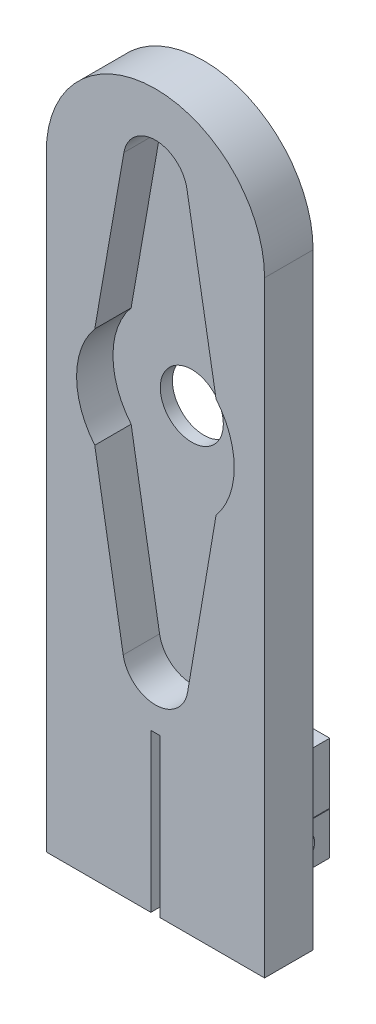
SolidWorks part; units mm, degrees
ref_plane "前基準面" through (0, 0, 0) normal (0, 0, 1) x (1, 0, 0)
ref_plane "上基準面" through (0, 0, 0) normal (0, 1, 0) x (1, 0, 0)
ref_plane "右基準面" through (0, 0, 0) normal (1, 0, 0) x (0, 0, -1)
sketch "草圖1" plane through (0, 0, 0) normal (0, 0, 1) x (1, 0, 0)
  line L0 (-9, 0) -> (-9, 50)
  line L1 (0, 45.5769) -> (0, 0) construction
  line L2 (-9, 0) -> (9, 0)
  line L3 (9, 0) -> (9, 50)
  arc A0 (-9, 50) -> (9, 50) centre (0, 50) cw
  dimension "D1" = 18
  dimension "D2" = 50
extrude "填料-伸長1" add sketch "草圖1" along normal blind 4 contours L3 A0 L0 L2
sketch "草圖2" plane through (0, 0, 4) normal (0, 0, 1) x (1, 0, 0)
  line L0 (-2.6, 53.1451) -> (-5, 39.3524)
  line L1 (2.6, 53.1451) -> (5, 39.3524)
  line L2 (-5, 31.0457) -> (-2.6563, 17.2433)
  line L3 (5, 31.0457) -> (2.6563, 17.2433)
  line L5 (0, 0) -> (0, 15) construction
  line L6 (0, 55.3318) -> (0, 46.5984) construction
  line L7 (0, 15.3887) -> (0, 39.6759) construction
  line L8 (-9, 0) -> (9, 0) construction
  arc A0 (-2.6563, 17.2433) -> (2.6563, 17.2433) centre (0, 17.6943) ccw
  arc A1 (2.6, 53.1451) -> (-2.6, 53.1451) centre (0, 52.6927) ccw
  arc A2 (5, 31.0457) -> (5, 39.3524) centre (0, 35.199) ccw
  arc A3 (-5, 39.3524) -> (-5, 31.0457) centre (0, 35.199) ccw
  dimension "D1" = 15
  dimension "D2" = 13
  dimension "D4" = 2.6
  dimension "D3" = 14
  dimension "D5" = 5
  dimension "D6" = 5
extrude "除料-伸長1" cut sketch "草圖2" against normal blind 3 contours L3 A0 L2 A3 L0 A1 L1 A2
sketch "草圖4" plane through (0, 0, 0) normal (0, 0, 1) x (1, 0, 0)
  line L0 (-9, 34.8563) -> (9, 34.8563) construction
  line L1 (-9, 0) -> (-9, 50) construction
  line L2 (9, 0) -> (9, 50) construction
  line L3 (0, 0) -> (0, 59) construction
  line L4 (0, 15.3887) -> (0, 39.6759) construction
  arc A0 (9, 50) -> (-9, 50) centre (0, 50) ccw construction
  circle A1 centre (0, 34.8563) radius 2.6
  point P14 (0, 34.5661)
  point P17 (0, 34.6383)
  point P18 (0, 34.8563)
  dimension "D1" = 5.2
extrude "除料-伸長9" cut sketch "草圖4" against normal blind 2 and the other way blind 19
sketch "草圖5" plane through (0, 0, 0) normal (0, 0, 1) x (1, 0, 0)
  line L0 (0, 0) -> (0, 15) construction
  line L1 (-9, 0) -> (9, 0) construction
  line L11 (-0.375, 0) -> (0.375, 0)
  line L12 (-0.375, 0) -> (-0.375, 13)
  line L13 (-0.375, 13) -> (0.375, 13)
  line L14 (0.375, 0) -> (0.375, 13)
  arc A0 (-2.6563, 17.2433) -> (2.6563, 17.2433) centre (0, 17.6943) ccw construction
  point P12 (0, 7.9974)
  dimension "D1" = 0.75
  dimension "D2" = 13
extrude "除料-伸長11" cut sketch "草圖5" along normal through all contours L12 L13 L14 L11
sketch "草圖8" plane through (0, 0, 0) normal (0, 0, 1) x (1, 0, 0)
  line L0 (0.375, 0) -> (0.375, 13) construction
  line L1 (5.375, 10.8122) -> (0.375, 10.8122)
  line L2 (5.375, 10.8122) -> (5.375, 5.8122)
  line L3 (5.375, 5.8122) -> (0.375, 5.8122)
  line L4 (0.375, 10.8122) -> (0.375, 5.8122)
  dimension "D1" = 5
  dimension "D2" = 5
extrude "填料-伸長2" add sketch "草圖8" against normal blind 5
sketch "草圖9" plane through (0, 0, 0) normal (1, 0, 0) x (0, 0, -1)
  line L0 (0, 8.3122) -> (4.7595, 8.3122) construction
  line L1 (0, 5.8122) -> (0, 10.8122) construction
  line L2 (2.5, 5.8122) -> (2.5, 7.7398) construction
  line L3 (5, 5.8122) -> (0, 5.8122) construction
  circle A0 centre (2.3798, 8.3122) radius 1.25
  dimension "D1" = 2.5
extrude "除料-伸長12" cut sketch "草圖9" along normal blind 39
ref_plane "平面1" through (0.375, 0, 0) normal (1, 0, 0) x (0, 0, -1)
sketch "草圖11" plane through (0.375, 0, 0) normal (1, 0, 0) x (0, 0, -1)
  line L0 (0, 0) -> (0, 50) construction
  line L1 (0, 5.7622) -> (5, 5.7622)
  line L2 (0, 5.7622) -> (0, 2.2622)
  line L3 (0, 2.2622) -> (5, 2.2622)
  line L4 (5, 5.7622) -> (5, 2.2622)
  line L6 (2.5, 5.7622) -> (2.5, 2.2622) construction
  line L7 (5, 4.0122) -> (0, 4.0122) construction
  circle A0 centre (2.5, 4.0122) radius 1.25
  circle A2 centre (2.3798, 8.3122) radius 1.25 construction
  dimension "D1" = 2.5
  dimension "D3" = 1.8
  dimension "D2" = 5
  dimension "D4" = 3.5
extrude "填料-伸長4" add sketch "草圖11" along normal blind 5
